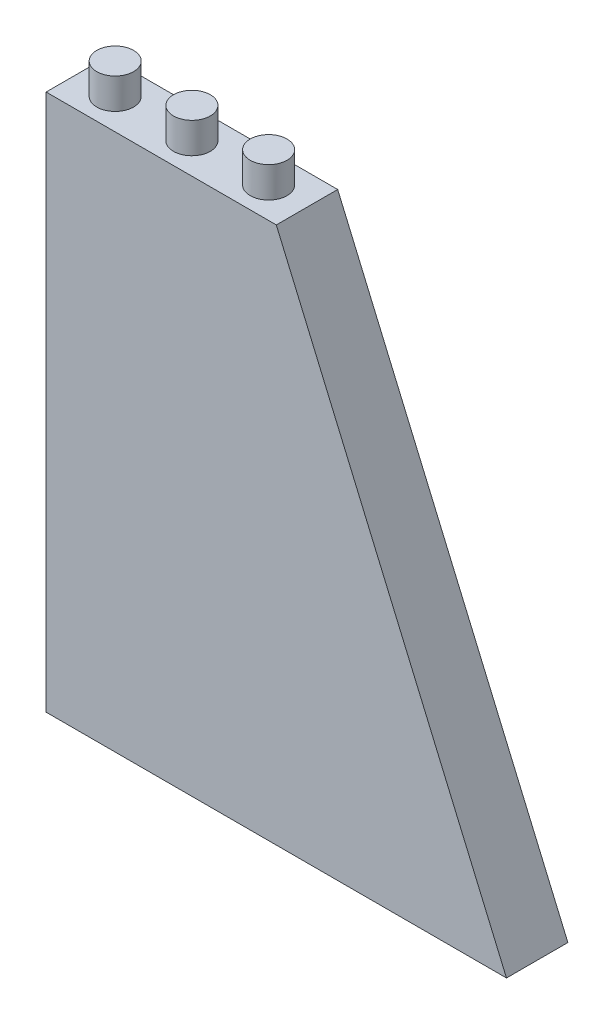
SolidWorks part; units mm, degrees
material "ABS"
ref_plane "Plano frontal" through (0, 0, 0) normal (0, 0, 1) x (1, 0, 0)
ref_plane "Plano superior" through (0, 0, 0) normal (0, 1, 0) x (1, 0, 0)
ref_plane "Plano direito" through (0, 0, 0) normal (1, 0, 0) x (0, 0, -1)
sketch "Esboço1" plane through (0, 0, 0) normal (0, 0, 1) x (1, 0, 0)
  line L0 (0, 0) -> (0, 70)
  line L1 (0, 70) -> (30, 70)
  line L2 (30, 70) -> (60, 0)
  line L3 (60, 0) -> (0, 0)
  dimension "D1" = 30
  dimension "D2" = 60
  dimension "D3" = 70
extrude "Ressalto-extrusão1" add sketch "Esboço1" along normal blind 8
sketch "Esboço2" plane through (0, 70, 0) normal (0, 1, 0) x (1, 0, 0)
  line L0 (0, -4) -> (10, -4) construction
  line L1 (0, -8) -> (0, 0) construction
  line L2 (10, -4) -> (20, -4) construction
  line L3 (20, -4) -> (30, -4) construction
  line L5 (30, -8) -> (30, 0) construction
  circle A0 centre (25, -4) radius 2.4
  circle A1 centre (15, -4) radius 2.4
  circle A2 centre (5, -4) radius 2.4
  point P11 (30, -4)
  dimension "D1" = 4.8
extrude "Ressalto-extrusão2" add sketch "Esboço2" along normal blind 4
